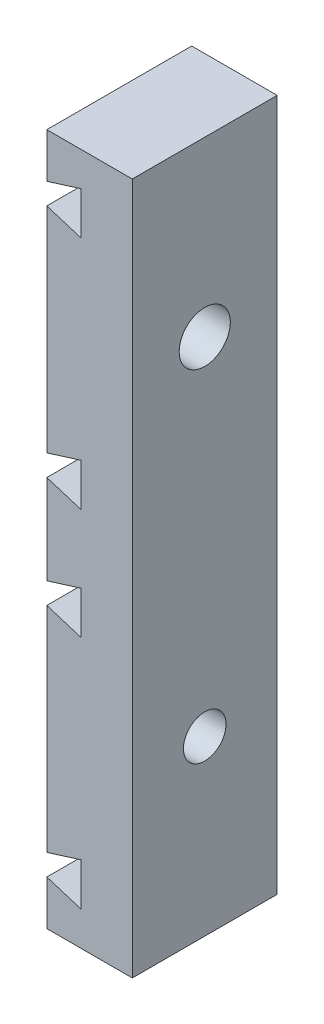
SolidWorks part; units mm, degrees
ref_plane "Alzado" through (0, 0, 0) normal (0, 0, 1) x (1, 0, 0)
ref_plane "Planta" through (0, 0, 0) normal (0, 1, 0) x (1, 0, 0)
ref_plane "Vista lateral" through (0, 0, 0) normal (1, 0, 0) x (0, 0, -1)
sketch "Croquis1" plane through (0, 0, 0) normal (0, 0, 1) x (1, 0, 0)
  line L5 (12.15, 8.15) -> (12.15, 5.65)
  line L16 (10.15, 10.15) -> (10.15, 7.525)
  line L17 (10.15, 10.15) -> (15.1656, 10.15)
  line L18 (15.1656, 10.15) -> (15.1656, -10.15)
  line L19 (12.15, 5.65) -> (10.15, 6.275)
  line L20 (12.15, 8.15) -> (10.15, 7.525)
  line L21 (12.15, -5.65) -> (10.15, -6.275)
  line L22 (12.15, -5.65) -> (12.15, -8.15)
  line L23 (12.15, -8.15) -> (10.15, -7.525)
  line L24 (10.15, 6.275) -> (10.15, -6.275)
  line L25 (10.15, -7.525) -> (10.15, -10.15)
  line L26 (15.1656, -10.15) -> (10.15, -10.15)
  point P12 (12.15, 6.9)
  dimension "D4" = 2.5
  dimension "D5" = 1.25
  dimension "D6" = 0.625
  dimension "D7" = 2
  dimension "D8" = 2
  dimension "D9" = 2
extrude "Saliente-Extruir1" add sketch "Croquis1" along normal blind 8.5
sketch "Croquis2" plane through (10.15, 0, 0) normal (-1, 0, 0) x (0, 0, 1)
  line L0 (8.5, 6.275) -> (0, 6.275) construction
  circle A0 centre (4.25, 0) radius 1.25
  point P5 (4.25, 6.275)
  dimension "D1" = 2.5
extrude "Cortar-Extruir1" cut sketch "Croquis2" against normal blind 8.5
sketch "Croquis3" plane through (10.15, 0, 0) normal (-1, 0, 0) x (0, 0, 1)
  circle A0 centre (4.25, 0) radius 3
  dimension "D1" = 6
extrude "Cortar-Extruir2" cut sketch "Croquis3" against normal blind 2.5
mirror "Simetría1" about plane through (10.15, 10.15, 8.5) normal (0, -1, 0) of "Saliente-Extruir1"
sketch "Croquis4" plane through (10.15, 0, 0) normal (-1, 0, 0) x (0, 0, 1)
  line L0 (0, 14.025) -> (0, 26.575) construction
  line L2 (8.5, 14.025) -> (0, 14.025) construction
  circle A1 centre (4.25, 20.3) radius 1.5
  point P2 (0, 0)
  point P5 (0, 20.3)
  point P8 (4.25, 14.025)
  point P9 (0, 0)
  dimension "D1" = 3
extrude "Cortar-Extruir3" cut sketch "Croquis4" against normal through all both and the other way through all
sketch "Croquis5" plane through (10.15, 0, 0) normal (-1, 0, 0) x (0, 0, 1)
  circle A0 centre (4.25, 20.3) radius 3
  dimension "D1" = 6
extrude "Cortar-Extruir4" cut sketch "Croquis5" against normal blind 2.5
